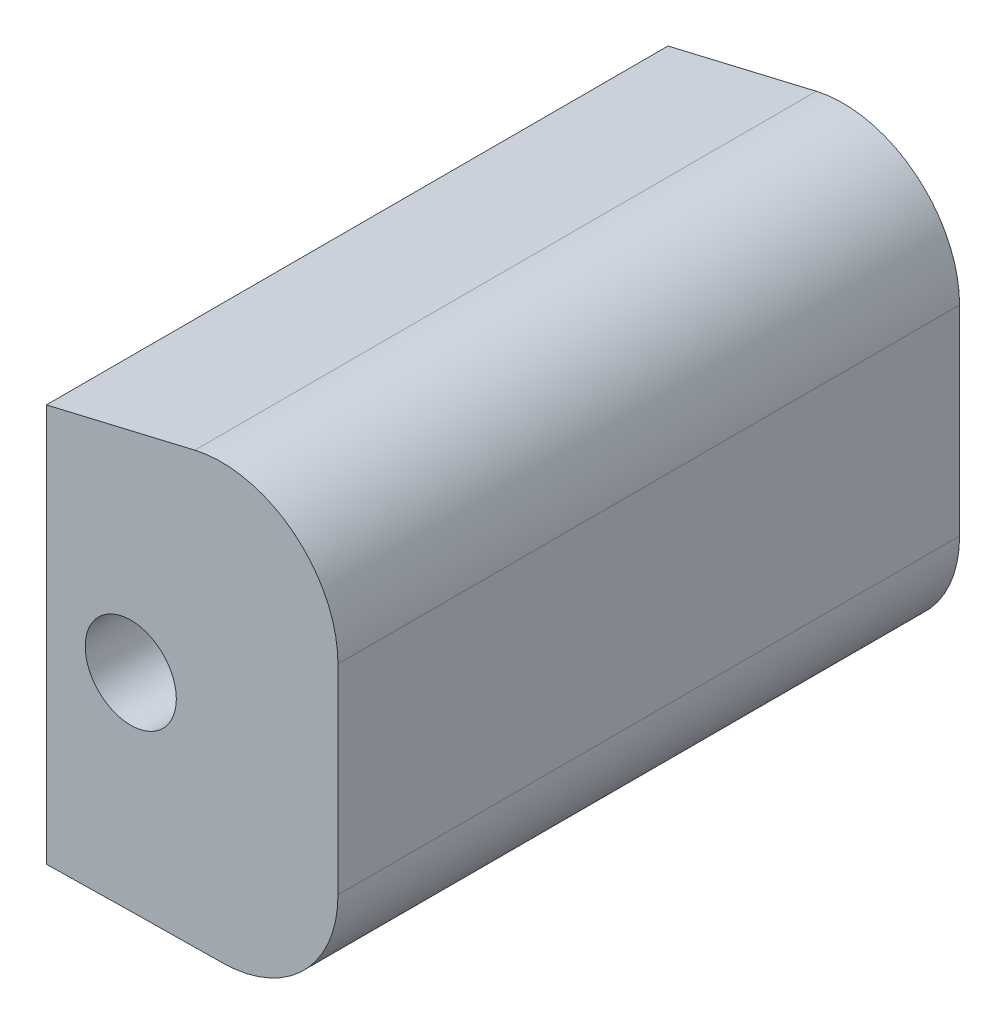
SolidWorks part; units mm, degrees
ref_plane "Front Plane" through (0, 0, 0) normal (0, 0, 1) x (1, 0, 0)
ref_plane "Top Plane" through (0, 0, 0) normal (0, 1, 0) x (1, 0, 0)
ref_plane "Right Plane" through (0, 0, 0) normal (1, 0, 0) x (0, 0, -1)
sketch "Sketch1" plane through (0, 0, 0) normal (0, 0, 1) x (1, 0, 0)
  line L0 (42.9183, -0.4477) -> (42.9183, 8.2631)
  circle A0 centre (-19.1025, -6.0109) radius 2.127
  circle A1 centre (12.6475, 4.4031) radius 2.127
  arc A2 (37.8951, -5.5274) -> (42.9183, -0.4477) centre (37.8383, -0.4477) ccw
  arc A3 (42.9183, 8.2631) -> (36.6811, 13.2095) centre (37.8383, 8.2631) ccw
  circle A4 centre (33.8935, 3.4217) radius 1.9844
  spline S0 degree 3 poles (36.6811, 13.2095) (19.8298, 9.2672) (-2.0736, 3.8441) (-31.0965, -5.5459) (-39.3168, -8.8066) (-49.5156, -12.4957) (-45.7725, -12.1069) knots 0.118069 0.118069 0.118069 0.118069 0.630725 0.824214 0.940085 1 1 1 1
  spline S1 degree 3 poles (-45.7725, -12.1069) (-41.3374, -10.9993) (-33.8316, -10.53) (-20.4835, -8.7075) (-8.8734, -8.0192) (11.5246, -6.0282) (26.0673, -5.6598) (37.8951, -5.5274) knots 0 0 0 0 0.144322 0.237948 0.427123 0.512832 0.887818 0.887818 0.887818 0.887818
  dimension "D2" = 3.9688
  dimension "D1" = 83.6676
extrude "Boss-Extrude1" add sketch "Sketch1" along normal blind 27.0764
sketch "Sketch2" plane through (0, 0, 27.0764) normal (0, 0, 1) x (1, 0, 0)
  line L1 (-58.5048, 14.1188) -> (30.2183, 14.1188)
  line L2 (-58.5048, 14.1188) -> (-58.5048, -18.8296)
  line L3 (-58.5048, -18.8296) -> (30.2183, -18.8296)
  line L4 (30.2183, 14.1188) -> (30.2183, -18.8296)
  dimension "D1" = 12.7
extrude "Cut-Extrude1" cut sketch "Sketch2" against normal blind 27.0764
